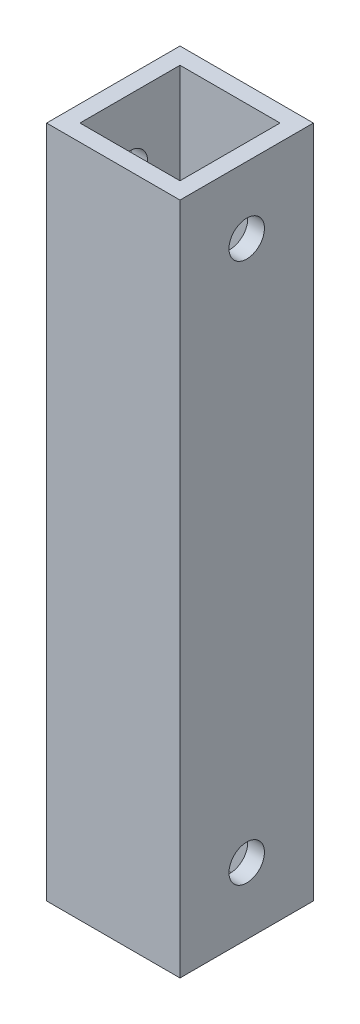
SolidWorks part; units mm, degrees
ref_plane "Front Plane" through (0, 0, 0) normal (0, 0, 1) x (1, 0, 0)
ref_plane "Top Plane" through (0, 0, 0) normal (0, 1, 0) x (1, 0, 0)
ref_plane "Right Plane" through (0, 0, 0) normal (1, 0, 0) x (0, 0, -1)
sketch "Sketch1" plane through (0, 0, 0) normal (0, 1, 0) x (1, 0, 0)
  line L0 (-9.525, 9.525) -> (9.525, 9.525)
  line L1 (-12.7, -12.7) -> (12.7, -12.7)
  line L2 (-12.7, -12.7) -> (-12.7, 12.7)
  line L3 (-12.7, 12.7) -> (12.7, 12.7)
  line L4 (12.7, -12.7) -> (12.7, 12.7)
  line L5 (-12.7, -12.7) -> (12.7, 12.7) construction
  line L6 (-12.7, 12.7) -> (12.7, -12.7) construction
  line L7 (9.525, -9.525) -> (9.525, 9.525)
  line L8 (-9.525, -9.525) -> (9.525, -9.525)
  line L9 (-9.525, -9.525) -> (-9.525, 9.525)
  point P0 (0, 0)
  dimension "D1" = 25.4
  dimension "D2" = 3.175
extrude "Boss-Extrude1" add sketch "Sketch1" along normal blind 128.27
sketch "Sketch2" plane through (0, 0, -12.7) normal (0, 0, -1) x (-1, 0, 0)
  line L0 (41.6855, 102.9716) -> (41.6855, 25.4) construction
  line L1 (41.6855, 38.1) -> (-5.08, 38.1)
  line L2 (41.6855, 38.1) -> (41.6855, 50.8)
  line L3 (41.6855, 50.8) -> (-5.08, 50.8)
  line L4 (-5.08, 38.1) -> (-5.08, 50.8)
  line L5 (-12.7, 0) -> (12.7, 0) construction
  line L6 (-12.7, 128.27) -> (-12.7, 0) construction
  dimension "D1" = 12.7
  dimension "D2" = 38.1
  dimension "D3" = 7.62
extrude "Cut-Extrude1" cut sketch "Sketch2" against normal blind 12.7
sketch "Sketch4" plane through (12.7, 0, 0) normal (1, 0, 0) x (0, 0, -1)
  line L0 (-12.7, 0) -> (12.7, 0) construction
  line L1 (-12.7, 128.27) -> (12.7, 128.27) construction
  circle A0 centre (0, 115.57) radius 3.3734
  circle A1 centre (0, 12.7) radius 3.3734
  dimension "D2" = 12.7
  dimension "D3" = 6.7469
  dimension "D4" = 6.7469
  dimension "D1" = 12.7
extrude "Cut-Extrude2" cut sketch "Sketch4" against normal through all
